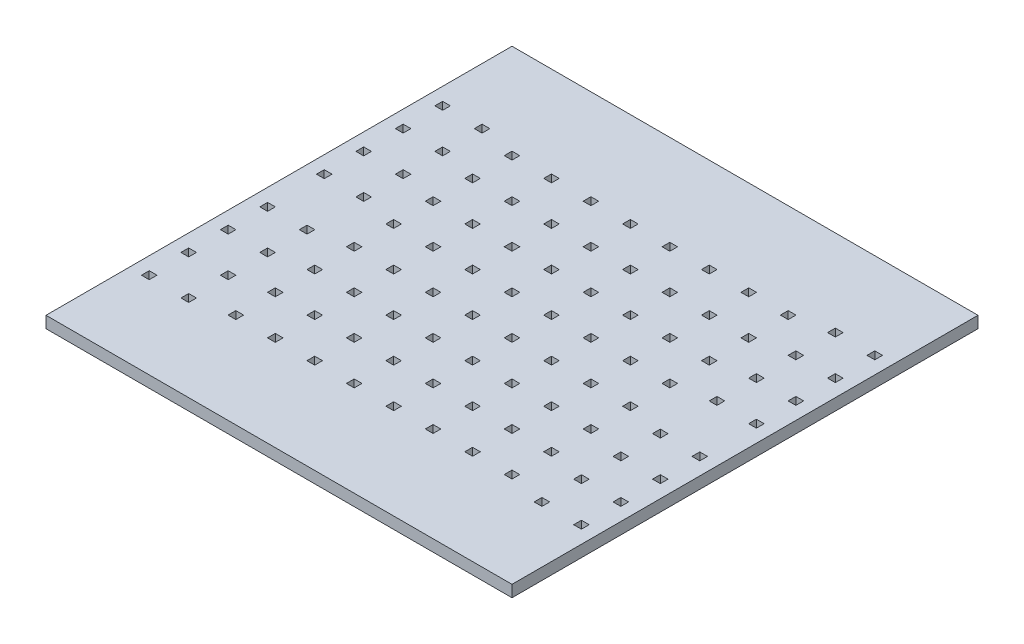
SolidWorks part; units mm, degrees
ref_plane "Front Plane" through (0, 0, 0) normal (0, 0, 1) x (1, 0, 0)
ref_plane "Top Plane" through (0, 0, 0) normal (0, 1, 0) x (1, 0, 0)
ref_plane "Right Plane" through (0, 0, 0) normal (1, 0, 0) x (0, 0, -1)
sketch "Sketch3" plane through (0, 0, 0) normal (0, 1, 0) x (1, 0, 0)
  line L1 (-300, -300) -> (300, -300)
  line L2 (-300, -300) -> (-300, 300)
  line L3 (-300, 300) -> (300, 300)
  line L4 (300, -300) -> (300, 300)
  line L5 (-300, -300) -> (300, 300) construction
  line L6 (-300, 300) -> (300, -300) construction
  point P0 (0, 0)
  dimension "D1" = 600
  dimension "D2" = 600
extrude "Boss-Extrude1" add sketch "Sketch3" along normal blind 15
sketch "Sketch4" plane through (0, 15, 0) normal (0, 1, 0) x (1, 0, 0)
  line L1 (203.4, 203.4) -> (-203.4, 203.4)
  line L2 (203.4, 203.4) -> (203.4, -203.4)
  line L3 (203.4, -203.4) -> (-203.4, -203.4)
  line L4 (-203.4, 203.4) -> (-203.4, -203.4)
  line L5 (203.4, 203.4) -> (-203.4, -203.4) construction
  line L6 (203.4, -203.4) -> (-203.4, 203.4) construction
  point P0 (0, 0)
  dimension "D1" = 406.8
  dimension "D2" = 406.8
sketch "Sketch5" plane through (0, 15, 0) normal (0, 1, 0) x (1, 0, 0)
  line L0 (203.4, 203.4) -> (-203.4, -203.4) construction
  line L1 (203.4, 203.4) -> (152.6, 203.4)
  line L2 (203.4, 203.4) -> (203.4, 152.6)
  line L3 (203.4, 152.6) -> (152.6, 152.6)
  line L4 (152.6, 203.4) -> (152.6, 152.6)
  circle A0 centre (178.0378, 178) radius 2.65
  dimension "D2" = 5.3
  dimension "D1" = 50.8
extrude "Cut-Extrude1" [suppressed] cut sketch "Sketch5" against normal blind 8.5 draft 1 contours A0
pattern_linear "LPattern1" [suppressed] count 8 spacing 50 along (-1, 0, 0) count 8 spacing 50 along (0, 0, 1)
sketch "Sketch8" plane through (0, 15, 0) normal (0, 1, 0) x (1, 0, 0)
  line L0 (203.4, -203.4) -> (-203.4, 203.4) construction
  line L1 (-203.4, 203.4) -> (-152.6, 203.4)
  line L2 (-203.4, 203.4) -> (-203.4, 152.6)
  line L3 (-203.4, 152.6) -> (-152.6, 152.6)
  line L4 (-152.6, 203.4) -> (-152.6, 152.6)
  point P7 (-178, 178)
  dimension "D1" = 50.8
sketch "Sketch10" plane through (0, 0, 0) normal (0, 1, 0) x (1, 0, 0)
  line L1 (-173, 173) -> (-183, 173)
  line L2 (-173, 173) -> (-173, 183)
  line L3 (-173, 183) -> (-183, 183)
  line L4 (-183, 173) -> (-183, 183)
  line L5 (-178, 183) -> (-178, 173) construction
  line L6 (-173, 178) -> (-183, 178) construction
  point P0 (-178, 178)
extrude "Cut-Extrude2" cut sketch "Sketch10" along normal through all
pattern_linear "LPattern2" count 8 spacing 50.8 along (1, 0, 0) count 8 spacing 50.8 along (0, 0, 1) of "Cut-Extrude2"
sketch "Sketch12" plane through (0, 15, 0) normal (0, 1, 0) x (1, 0, 0)
  line L1 (-300, 300) -> (-203.4, 300)
  line L2 (-300, 300) -> (-300, -203.4)
  line L3 (-300, -203.4) -> (-203.4, -203.4)
  line L4 (-203.4, 300) -> (-203.4, -203.4)
  line L5 (300, 300) -> (203.4, 300)
  line L6 (300, 300) -> (300, -203.4)
  line L7 (300, -203.4) -> (203.4, -203.4)
  line L8 (203.4, 300) -> (203.4, -203.4)
sketch "Sketch13" plane through (0, 15, 0) normal (0, 1, 0) x (1, 0, 0)
  line L1 (-222.4164, -183.8597) -> (-232.4164, -183.8597)
  line L2 (-222.4164, -183.8597) -> (-222.4164, -193.8597)
  line L3 (-222.4164, -193.8597) -> (-232.4164, -193.8597)
  line L4 (-232.4164, -183.8597) -> (-232.4164, -193.8597)
  dimension "D1" = 10
  dimension "D2" = 10
extrude "Cut-Extrude3" cut sketch "Sketch13" against normal through all
pattern_linear "LPattern3" count 2 spacing 50.8 along (-1, 0, 0) count 4 spacing 50.8 along (0, 0, -1) of "Cut-Extrude3"
ref_plane "Plane1" through (0, 0, 0) normal (1, 0, 0) x (0, 0, -1)
mirror "Mirror5" about plane through (0, 0, 0) normal (1, 0, 0) of "LPattern3", "Cut-Extrude3"
ref_plane "Plane2" through (0, 0, 0) normal (0, 0, -1) x (-1, 0, 0)
mirror "Mirror6" about plane through (0, 0, 0) normal (0, 0, -1) of "LPattern3", "Cut-Extrude3"
mirror "Mirror7" about plane through (0, 0, 0) normal (0, 0, -1) of "Mirror5"
